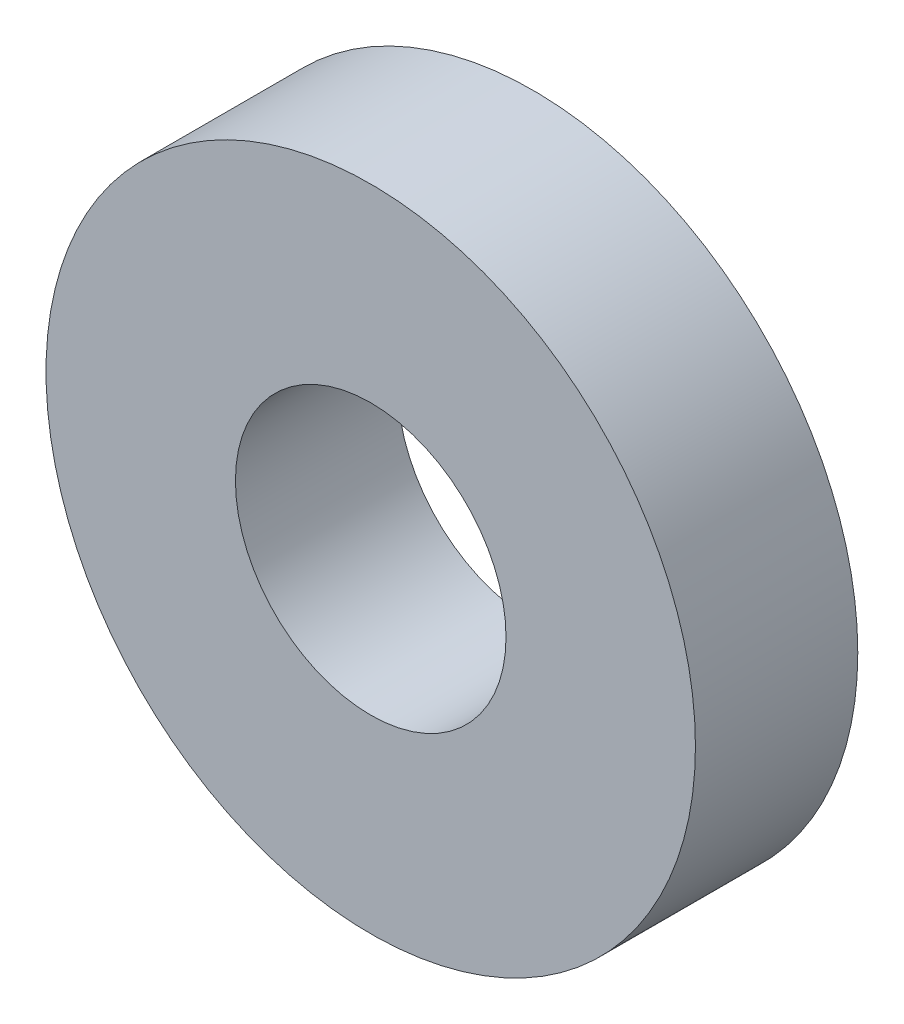
SolidWorks part; units mm, degrees
material "6061-T6 (SS)"
ref_plane "前视基准面" through (0, 0, 0) normal (0, 0, 1) x (1, 0, 0)
ref_plane "上视基准面" through (0, 0, 0) normal (0, 1, 0) x (1, 0, 0)
ref_plane "右视基准面" through (0, 0, 0) normal (1, 0, 0) x (0, 0, -1)
sketch "草图1" plane through (0, 0, 0) normal (0, 0, 1) x (1, 0, 0)
  circle A0 centre (0, 0) radius 12
  circle A1 centre (0, 0) radius 5
  dimension "D1" = 10
  dimension "D2" = 24
extrude "凸台-拉伸1" add sketch "草图1" along normal blind 6
